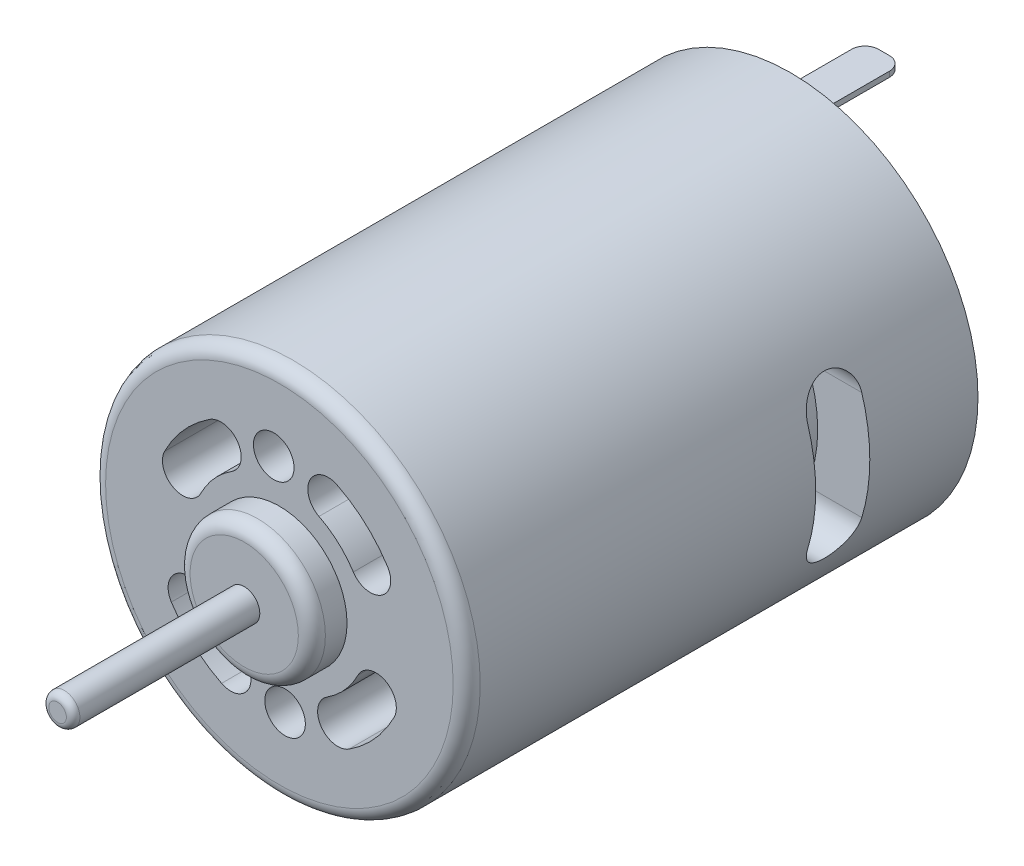
SolidWorks part; units mm, degrees
ref_plane "正面" through (0, 0, 0) normal (0, 0, 1) x (1, 0, 0)
ref_plane "平面" through (0, 0, 0) normal (0, 1, 0) x (1, 0, 0)
ref_plane "右側面" through (0, 0, 0) normal (1, 0, 0) x (0, 0, -1)
sketch "ｽｹｯﾁ1" plane through (0, 0, 0) normal (0, 0, 1) x (1, 0, 0)
  circle A0 centre (0, 0) radius 13.85
  dimension "D1" = 27.7
extrude "ﾎﾞｽ - 押し出し1" add sketch "ｽｹｯﾁ1" along normal blind 37.8
fillet "ﾌｨﾚｯﾄ1" radius 1 1 edges at (13.85, 0, 37.8)
sketch "ｽｹｯﾁ2" plane through (0, 0, 37.8) normal (0, 0, 1) x (1, 0, 0)
  circle A0 centre (0, 0) radius 5
  dimension "D1" = 10
extrude "ﾎﾞｽ - 押し出し2" add sketch "ｽｹｯﾁ2" along normal blind 2.6
fillet "ﾌｨﾚｯﾄ2" radius 1 1 edges at (5, 0, 40.4)
sketch "ｽｹｯﾁ3" plane through (0, 0, 40.4) normal (0, 0, 1) x (1, 0, 0)
  circle A0 centre (0, 0) radius 1.15
  dimension "D1" = 2.3
extrude "ﾎﾞｽ - 押し出し3" add sketch "ｽｹｯﾁ3" along normal blind 13.8
fillet "ﾌｨﾚｯﾄ3" radius 0.5 1 edges at (1.15, 0, 54.2)
sketch "ｽｹｯﾁ5" plane through (0, 0, 37.8) normal (0, 0, 1) x (1, 0, 0)
  line L0 (0, 0) -> (0, 12.85) construction
  line L1 (0, 12.85) -> (0, -12.85) construction
  line L2 (0, 0) -> (0.7249, -13.831) construction
  line L3 (0.7249, -13.831) -> (-0.7249, 13.831) construction
  line L4 (-5.9452, 5.353) -> (5.9452, -5.353) construction
  line L5 (5.353, 5.9452) -> (-5.353, -5.9452) construction
  circle A0 centre (0, 0) radius 12.85 construction
  circle A1 centre (0, 0) radius 13.85 construction
  circle A2 centre (-0.4187, 7.989) radius 1.5
  circle A3 centre (0.4187, -7.989) radius 1.5
  circle A4 centre (0, 0) radius 8 construction
  arc A5 (3.5998, 7.1443) -> (6.7289, 4.3269) centre (0, 0) cw construction
  arc A6 (7.9905, 5.1382) -> (4.2748, 8.4839) centre (0, 0) ccw
  arc A7 (5.4672, 3.5156) -> (2.9249, 5.8047) centre (0, 0) ccw
  arc A8 (5.4672, 3.5156) -> (7.9905, 5.1382) centre (6.7289, 4.3269) ccw
  arc A9 (4.2748, 8.4839) -> (2.9249, 5.8047) centre (3.5998, 7.1443) ccw
  arc A10 (7.1443, -3.5998) -> (4.3269, -6.7289) centre (0, 0) cw construction
  arc A11 (5.1382, -7.9905) -> (8.4839, -4.2748) centre (0, 0) ccw
  arc A12 (3.5156, -5.4672) -> (5.8047, -2.9249) centre (0, 0) ccw
  arc A13 (3.5156, -5.4672) -> (5.1382, -7.9905) centre (4.3269, -6.7289) ccw
  arc A14 (8.4839, -4.2748) -> (5.8047, -2.9249) centre (7.1443, -3.5998) ccw
  arc A15 (-3.5998, -7.1443) -> (-6.7289, -4.3269) centre (0, 0) cw construction
  arc A16 (-7.9905, -5.1382) -> (-4.2748, -8.4839) centre (0, 0) ccw
  arc A17 (-5.4672, -3.5156) -> (-2.9249, -5.8047) centre (0, 0) ccw
  arc A18 (-5.4672, -3.5156) -> (-7.9905, -5.1382) centre (-6.7289, -4.3269) ccw
  arc A19 (-4.2748, -8.4839) -> (-2.9249, -5.8047) centre (-3.5998, -7.1443) ccw
  arc A20 (-4.3269, 6.7289) -> (-7.1443, 3.5998) centre (0, 0) ccw construction
  arc A21 (-5.1382, 7.9905) -> (-8.4839, 4.2748) centre (0, 0) ccw
  arc A22 (-3.5156, 5.4672) -> (-5.8047, 2.9249) centre (0, 0) ccw
  arc A23 (-3.5156, 5.4672) -> (-5.1382, 7.9905) centre (-4.3269, 6.7289) ccw
  arc A24 (-8.4839, 4.2748) -> (-5.8047, 2.9249) centre (-7.1443, 3.5998) ccw
  point P19 (5.353, 5.9452)
  point P24 (5.9452, -5.353)
  point P32 (-5.353, -5.9452)
  point P40 (-5.9452, 5.353)
  dimension "D2" = 3
  dimension "D3" = 3
  dimension "D6" = 16
  dimension "D10" = 5
  dimension "D12" = 5
  dimension "D9" = 3
  dimension "D1" = 3
  dimension "D4" = 8
  dimension "D5" = 8
  dimension "D7" = 90
  dimension "D8" = 45
  dimension "D11" = 5
  dimension "D13" = 5
extrude "ｶｯﾄ - 押し出し1" cut sketch "ｽｹｯﾁ5" against normal blind 6
sketch "ｽｹｯﾁ6" plane through (0, 0, 0) normal (0, 0, -1) x (-1, 0, 0)
  circle A0 centre (0, 0) radius 5
  dimension "D1" = 10
extrude "ﾎﾞｽ - 押し出し4" add sketch "ｽｹｯﾁ6" along normal blind 2.6
fillet "ﾌｨﾚｯﾄ4" radius 1 1 edges at (-5, 0, -2.6)
sketch "ｽｹｯﾁ7" plane through (0, 0, 0) normal (0, 0, -1) x (-1, 0, 0)
  line L1 (-1.4, 11.7) -> (1.4, 11.7)
  line L2 (-1.4, 11.7) -> (-1.4, 11.3)
  line L3 (-1.4, 11.3) -> (1.4, 11.3)
  line L4 (1.4, 11.7) -> (1.4, 11.3)
  line L5 (-1.4, 11.7) -> (1.4, 11.3) construction
  line L6 (-1.4, 11.3) -> (1.4, 11.7) construction
  line L7 (-1.4, -11.3) -> (1.4, -11.3)
  line L8 (-1.4, -11.3) -> (-1.4, -11.7)
  line L9 (-1.4, -11.7) -> (1.4, -11.7)
  line L10 (1.4, -11.3) -> (1.4, -11.7)
  line L11 (-1.4, -11.3) -> (1.4, -11.7) construction
  line L12 (-1.4, -11.7) -> (1.4, -11.3) construction
  circle A0 centre (0, 0) radius 11.5 construction
  point P3 (0, 11.5)
  point P8 (0, -11.5)
  dimension "D1" = 23
  dimension "D2" = 2.8
  dimension "D3" = 0.4
  dimension "D4" = 2.8
  dimension "D5" = 0.4
extrude "ﾎﾞｽ - 押し出し5" add sketch "ｽｹｯﾁ7" along normal blind 6.9
fillet "ﾌｨﾚｯﾄ5" radius 1 4 edges at (1.4, -11.5, -6.9) (-1.4, -11.5, -6.9) (1.4, 11.5, -6.9) (-1.4, 11.5, -6.9)
sketch "ｽｹｯﾁ10" plane through (0, 0, 0) normal (1, 0, 0) x (0, 0, -1)
  line L0 (0, 0) -> (-40.4, 0) construction
  line L1 (-26.8, 5) -> (-20.8, 5)
  line L2 (-26.8, 5) -> (-26.8, 2)
  line L3 (-26.8, 2) -> (-17.8, 2)
  line L4 (-17.8, 3.5) -> (-17.8, 2)
  line L5 (-26.8, 5) -> (-17.8, 2) construction
  line L6 (-26.8, 2) -> (-17.8, 5) construction
  line L7 (-26.8, -2) -> (-17.8, -2)
  line L8 (-26.8, -2) -> (-26.8, -5)
  line L9 (-26.8, -5) -> (-20.8, -5)
  line L10 (-17.8, -2) -> (-17.8, -3.5)
  line L11 (-26.8, -2) -> (-17.8, -5) construction
  line L12 (-26.8, -5) -> (-17.8, -2) construction
  line L13 (0, -13.85) -> (0, 13.85) construction
  line L14 (-40.4, 4) -> (-40.4, -4) construction
  line L15 (-37.8, 12.85) -> (-37.8, -12.85) construction
  line L16 (-37.8, 5) -> (-37.8, -5) construction
  line L17 (-17.8, 3.5) -> (-20.8, 5)
  line L18 (-17.8, -3.5) -> (-20.8, -5)
  point P0 (-22.3, 3.5)
  point P5 (-22.3, -3.5)
  dimension "D1" = 4
  dimension "D2" = 2
  dimension "D3" = 3
  dimension "D4" = 3
  dimension "D5" = 9
  dimension "D6" = 9
  dimension "D7" = 11
  dimension "D8" = 11
  dimension "D9" = 1.5
  dimension "D10" = 1.5
  dimension "D11" = 6
  dimension "D12" = 6
  dimension "D13" = 3.3541
  dimension "D14" = 3.3541
  dimension "D15" = 9.4868
  dimension "D16" = 9.4868
extrude "ｶｯﾄ - 押し出し3" cut sketch "ｽｹｯﾁ10" against normal through all
sketch "ｽｹｯﾁ11" plane through (0, 0, 0) normal (0, 0, -1) x (-1, 0, 0)
  line L0 (-13.7048, 2) -> (-2, 13.7048)
  line L1 (-13.7048, -2) -> (-2, -13.7048)
  line L2 (13.7048, 2) -> (2, 13.7048)
  line L3 (13.7048, -2) -> (2, -13.7048)
  line L4 (0, 0) -> (13.85, 0) construction
  line L5 (13.85, 0) -> (-19.8939, 0) construction
  line L6 (0, 13.85) -> (0, -13.85) construction
  circle A0 centre (0, 0) radius 13.85 construction
  arc A1 (-13.7048, 2) -> (-13.7048, -2) centre (0, 0) ccw
  arc A2 (-2, -13.7048) -> (2, -13.7048) centre (0, 0) ccw
  arc A3 (13.7048, 2) -> (13.7048, -2) centre (0, 0) cw
  arc A4 (-2, 13.7048) -> (2, 13.7048) centre (0, 0) cw
  dimension "D1" = 4
  dimension "D2" = 4
  dimension "D3" = 4
  dimension "D4" = 4
  dimension "D5" = 2
  dimension "D6" = 2
  dimension "D7" = 2
  dimension "D8" = 2
extrude "ﾎﾞｽ - 押し出し7" add sketch "ｽｹｯﾁ11" against normal blind 30
sketch "ｽｹｯﾁ8" plane through (0, 0, 0) normal (1, 0, 0) x (0, 0, -1)
  line L0 (-10, 4) -> (-10, -4) construction
  line L1 (-8, 4) -> (-8, -4)
  line L2 (-12, 4) -> (-12, -4)
  line L3 (0, -13.85) -> (0, 13.85) construction
  arc A0 (-8, 4) -> (-12, 4) centre (-10, 4) ccw
  arc A1 (-12, -4) -> (-8, -4) centre (-10, -4) ccw
  point P2 (-10, 0)
  dimension "D1" = 10
  dimension "D2" = 4
  dimension "D3" = 8
extrude "ｶｯﾄ - 押し出し2" cut sketch "ｽｹｯﾁ8" against normal through all and the other way through all
sketch "ｽｹｯﾁ9" plane through (0, 0, 0) normal (0, 0, -1) x (-1, 0, 0)
  circle A0 centre (0, 0) radius 10
  dimension "D1" = 20
extrude "ﾎﾞｽ - 押し出し6" add sketch "ｽｹｯﾁ9" against normal blind 20
